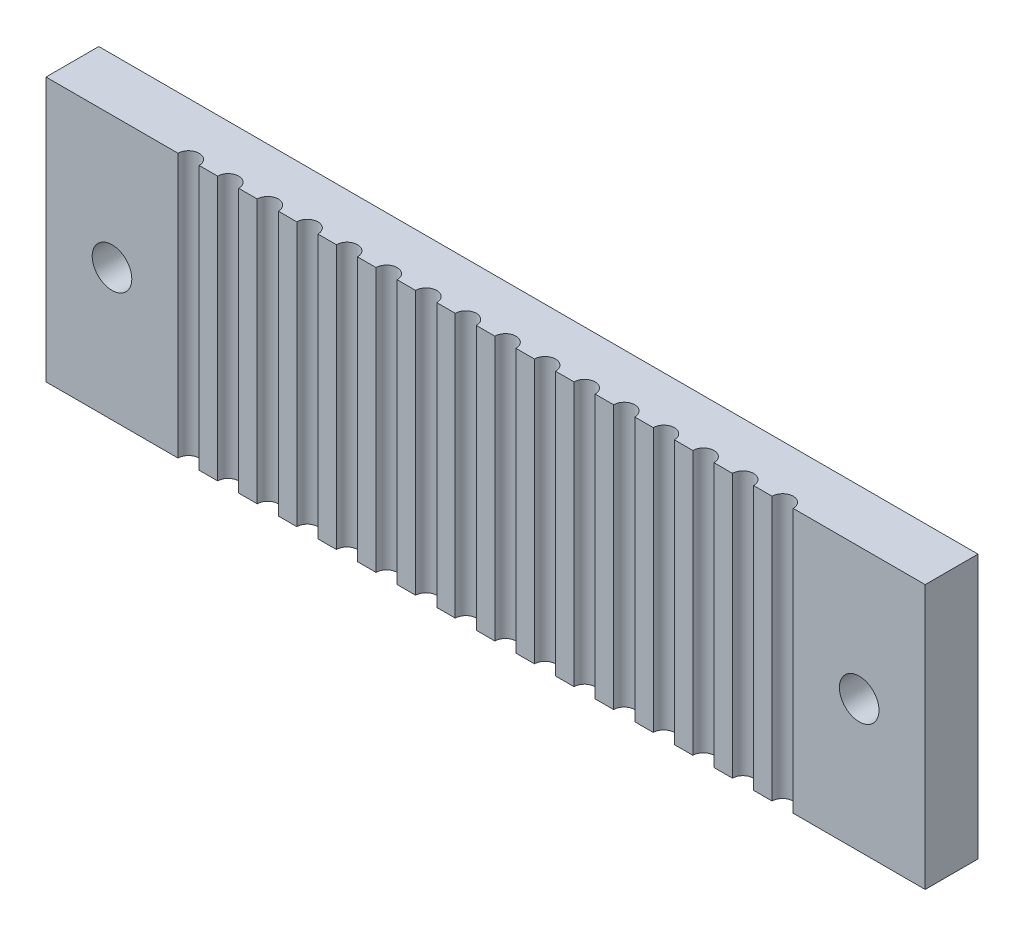
SolidWorks part; units mm, degrees
ref_plane "前视基准面" through (0, 0, 0) normal (0, 0, 1) x (1, 0, 0)
ref_plane "上视基准面" through (0, 0, 0) normal (0, 1, 0) x (1, 0, 0)
ref_plane "右视基准面" through (0, 0, 0) normal (1, 0, 0) x (0, 0, -1)
other "Configuration Table"
sketch "草图1" plane through (0, 0, 0) normal (0, 1, 0) x (1, 0, 0)
  line L0 (-10.8, 0) -> (-0.8, 0)
  line L1 (-10.8, 0) -> (-10.8, 4)
  line L2 (-10.8, 4) -> (55.8, 4)
  line L3 (55.8, 4) -> (55.8, 0)
  line L4 (3.8, 0) -> (5.2, 0)
  line L5 (0.8, 0) -> (2.2, 0)
  line L6 (6.8, 0) -> (8.2, 0)
  line L7 (9.8, 0) -> (11.2, 0)
  line L8 (12.8, 0) -> (14.2, 0)
  line L9 (15.8, 0) -> (17.2, 0)
  line L10 (18.8, 0) -> (20.2, 0)
  line L11 (21.8, 0) -> (23.2, 0)
  line L12 (24.8, 0) -> (26.2, 0)
  line L13 (27.8, 0) -> (29.2, 0)
  line L14 (30.8, 0) -> (32.2, 0)
  line L15 (33.8, 0) -> (35.2, 0)
  line L16 (36.8, 0) -> (38.2, 0)
  line L17 (39.8, 0) -> (41.2, 0)
  line L18 (42.8, 0) -> (44.2, 0)
  line L19 (45.8, 0) -> (55.8, 0)
  arc A0 (0.8, 0) -> (-0.8, 0) centre (0, 0) ccw
  arc A1 (3.8, 0) -> (2.2, 0) centre (3, 0) ccw
  arc A2 (6.8, 0) -> (5.2, 0) centre (6, 0) ccw
  arc A3 (9.8, 0) -> (8.2, 0) centre (9, 0) ccw
  arc A4 (12.8, 0) -> (11.2, 0) centre (12, 0) ccw
  arc A5 (15.8, 0) -> (14.2, 0) centre (15, 0) ccw
  arc A6 (18.8, 0) -> (17.2, 0) centre (18, 0) ccw
  arc A7 (21.8, 0) -> (20.2, 0) centre (21, 0) ccw
  arc A8 (24.8, 0) -> (23.2, 0) centre (24, 0) ccw
  arc A9 (27.8, 0) -> (26.2, 0) centre (27, 0) ccw
  arc A10 (30.8, 0) -> (29.2, 0) centre (30, 0) ccw
  arc A11 (33.8, 0) -> (32.2, 0) centre (33, 0) ccw
  arc A12 (36.8, 0) -> (35.2, 0) centre (36, 0) ccw
  arc A13 (39.8, 0) -> (38.2, 0) centre (39, 0) ccw
  arc A14 (42.8, 0) -> (41.2, 0) centre (42, 0) ccw
  arc A15 (45.8, 0) -> (44.2, 0) centre (45, 0) ccw
  dimension "D1" = 1.6
  dimension "D3" = 10.8
  dimension "D4" = 10.8
  dimension "D5" = 4
  dimension "D2" = 16
extrude "凸台-拉伸1" add sketch "草图1" along normal blind 20
sketch "草图2" plane through (0, 0, 0) normal (0, 0, 1) x (1, 0, 0)
  line L0 (-10.8, 10) -> (-5.8, 10) construction
  line L1 (-10.8, 20) -> (-10.8, 0) construction
  line L2 (55.8, 10) -> (50.8, 10) construction
  line L3 (55.8, 20) -> (55.8, 0) construction
  circle A0 centre (-5.8, 10) radius 1.5
  circle A1 centre (50.8, 10) radius 1.5
  dimension "D3" = 3
  dimension "D4" = 3
  dimension "D1" = 5
  dimension "D2" = 5
extrude "切除-拉伸1" cut sketch "草图2" against normal blind 10
